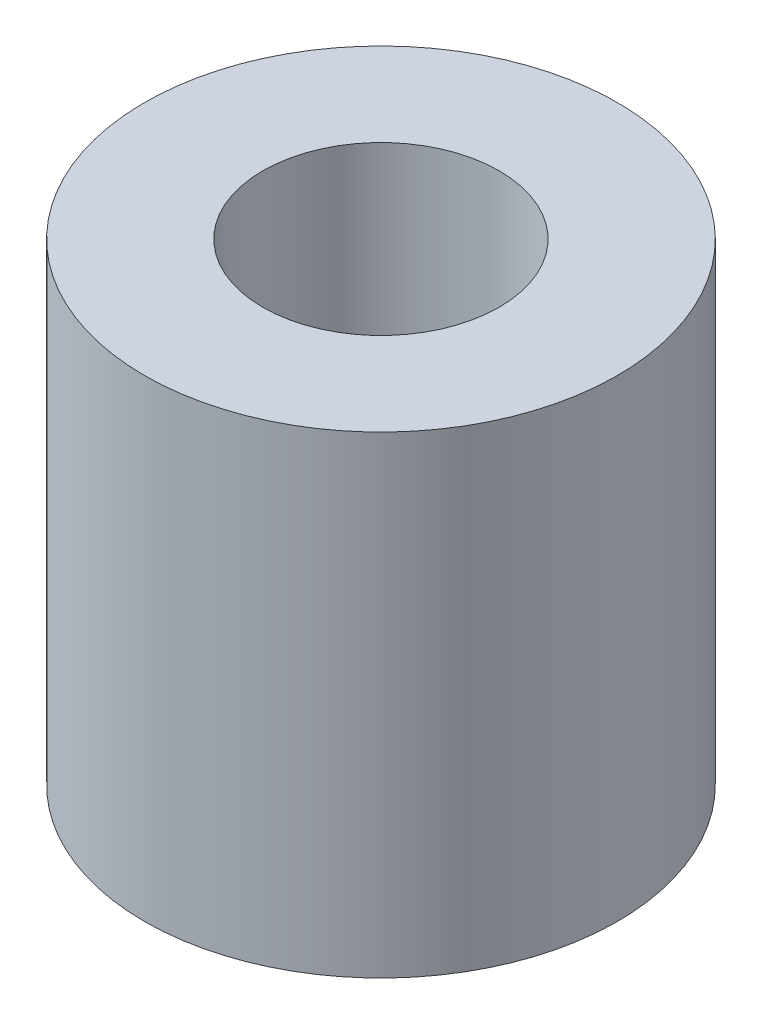
SolidWorks part; units mm, degrees
ref_plane "Front Plane" through (0, 0, 0) normal (0, 0, 1) x (1, 0, 0)
ref_plane "Top Plane" through (0, 0, 0) normal (0, 1, 0) x (1, 0, 0)
ref_plane "Right Plane" through (0, 0, 0) normal (1, 0, 0) x (0, 0, -1)
sketch "Sketch1" plane through (0, 0, 0) normal (0, 1, 0) x (1, 0, 0)
  circle A0 centre (0, 0) radius 3
  circle A1 centre (0, 0) radius 1.5
  dimension "D1" = 6
  dimension "D2" = 3
extrude "Boss-Extrude1" add sketch "Sketch1" along normal blind 6
